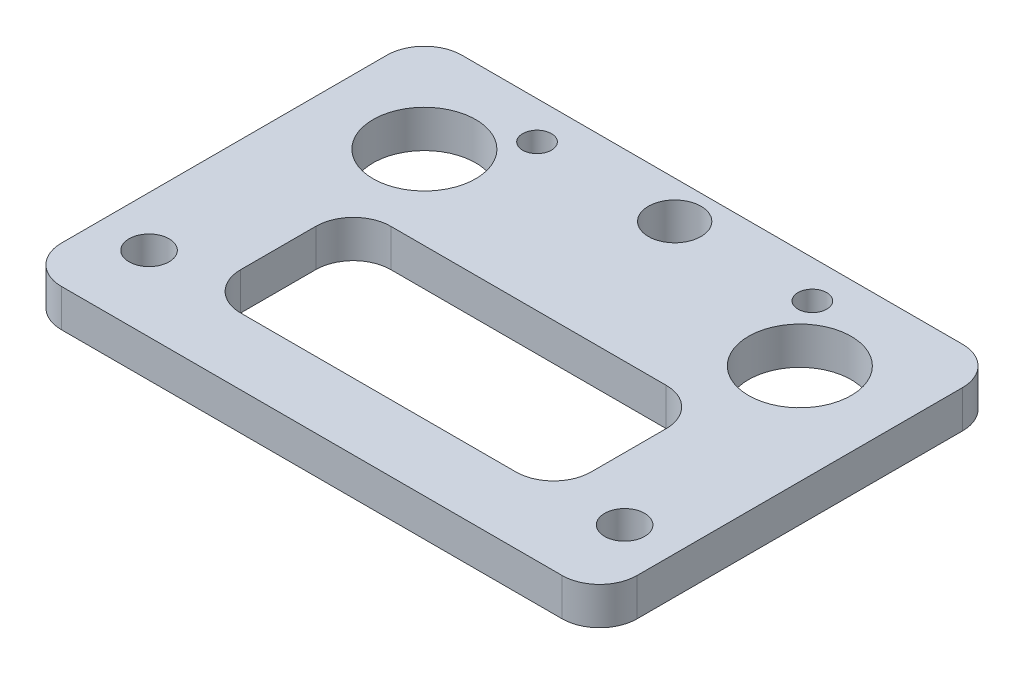
SolidWorks part; units mm, degrees
ref_plane "前视基准面" through (0, 0, 0) normal (0, 0, 1) x (1, 0, 0)
ref_plane "上视基准面" through (0, 0, 0) normal (0, 1, 0) x (1, 0, 0)
ref_plane "右视基准面" through (0, 0, 0) normal (1, 0, 0) x (0, 0, -1)
other "Configuration Table"
sketch "草图4" plane through (0, 0, 0) normal (0, 1, 0) x (1, 0, 0)
  line L1 (-23, 8) -> (23, 8)
  line L2 (-23, 8) -> (-23, -8)
  line L3 (-23, -8) -> (23, -8)
  line L4 (23, 8) -> (23, -8)
  line L5 (-23, 8) -> (23, -8) construction
  line L6 (-23, -8) -> (23, 8) construction
  point P0 (0, 0)
  dimension "D1" = 46
  dimension "D2" = 16
extrude "凸台-拉伸3" add sketch "草图4" along normal blind 3
sketch "草图5" plane through (0, 3, 0) normal (0, 1, 0) x (1, 0, 0)
  line L0 (-23, 0) -> (23, 0) construction
  line L1 (-23, 8) -> (-23, -8) construction
  line L2 (23, -8) -> (23, 8) construction
  line L3 (23, 8) -> (-23, 8) construction
  circle A0 centre (-15, 0) radius 4.1
  circle A1 centre (15, 0) radius 4.1
  dimension "D2" = 8.2
  dimension "D3" = 8.2
  dimension "D4" = 8
  dimension "D5" = 8
  dimension "D6" = 30
  dimension "D1" = 8
extrude "切除-拉伸1" cut sketch "草图5" against normal up to next
sketch "草图6" plane through (0, 0, 8) normal (0, 0, 1) x (1, 0, 0)
  line L1 (-23, 3) -> (23, 3)
  line L2 (-23, 3) -> (-23, 0)
  line L3 (-23, 0) -> (23, 0)
  line L4 (23, 3) -> (23, 0)
extrude "凸台-拉伸4" add sketch "草图6" along normal blind 16
sketch "草图9" plane through (0, 3, 0) normal (0, 1, 0) x (1, 0, 0)
  line L0 (23, -24) -> (23, 8) construction
  line L1 (-23, -24) -> (23, -24) construction
  line L2 (-23, -24) -> (-23, -8) construction
  line L3 (-23, -8) -> (23, -8) construction
  line L4 (23, -24) -> (23, -8) construction
  circle A0 centre (-15, 0) radius 4.1 construction
  circle A1 centre (-19, -18) radius 1.6
  circle A2 centre (19, -18) radius 1.6
  dimension "D3" = 3.2
  dimension "D4" = 4
  dimension "D5" = 6
  dimension "D7" = 3.2
  dimension "D8" = 4
  dimension "D9" = 6
  dimension "D10" = 38
  dimension "D1" = 8
  dimension "D2" = 46
  dimension "D6" = 2
extrude "切除-拉伸2" cut sketch "草图9" against normal up to next
sketch "草图11" plane through (0, 3, 0) normal (0, 1, 0) x (1, 0, 0)
  line L0 (-17.2441, 5) -> (16.7327, 5) construction
  line L1 (15, 8) -> (-15, 8) construction
  line L2 (0, 8) -> (0, -24) construction
  line L5 (15, -24) -> (-15, -24) construction
  circle A0 centre (-11, 5) radius 1.15
  circle A1 centre (11, 5) radius 1.15
  circle A2 centre (0, 5) radius 2.1
  point P12 (0, 5)
  dimension "D2" = 2.3
  dimension "D3" = 11
  dimension "D4" = 22
  dimension "D5" = 4.2
  dimension "D1" = 3
extrude "切除-拉伸4" cut sketch "草图11" against normal up to next
sketch "草图12" plane through (0, 3, 0) normal (0, 1, 0) x (1, 0, 0)
  line L0 (-15, 0) -> (15, -15.3616) construction
  line L1 (-15, 0) -> (15, 0) construction
  line L2 (-15, 0) -> (-15, -15.3616) construction
  line L3 (-15, -15.3616) -> (15, -15.3616) construction
  line L4 (15, 0) -> (15, -15.3616) construction
  line L5 (15, 0) -> (-15, -15.3616) construction
  line L6 (0, -7.6808) -> (0, -25.2649) construction
  line L10 (-14, -6.6808) -> (14, -6.6808)
  line L11 (-14, -6.6808) -> (-14, -18.6808)
  line L12 (-14, -18.6808) -> (14, -18.6808)
  line L13 (14, -6.6808) -> (14, -18.6808)
  line L14 (-14, -6.6808) -> (14, -18.6808) construction
  line L15 (-14, -18.6808) -> (14, -6.6808) construction
  point P7 (0, -12.6808)
  dimension "D1" = 30
  dimension "D2" = 5
  dimension "D3" = 28
  dimension "D4" = 12
extrude "切除-拉伸5" cut sketch "草图12" against normal up to next
fillet "圆角3" radius 3 8 edges at (-23, 1.5, 24) (23, 1.5, 24) (23, 1.5, -8) (-23, 1.5, -8) (14, 1.5, 18.6808) (14, 1.5, 6.6808) (-14, 1.5, 18.6808) (-14, 1.5, 6.6808)
